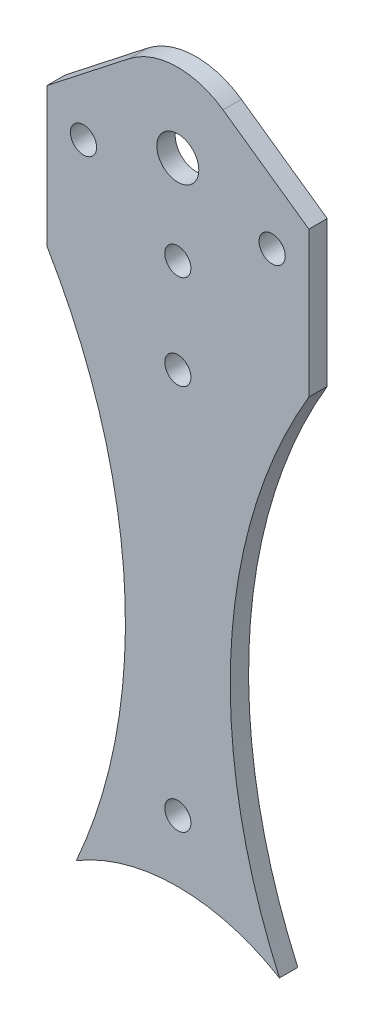
SolidWorks part; units mm, degrees
material "Cedar"
ref_plane "Front Plane" through (0, 0, 0) normal (0, 0, 1) x (1, 0, 0)
ref_plane "Top Plane" through (0, 0, 0) normal (0, 1, 0) x (1, 0, 0)
ref_plane "Right Plane" through (0, 0, 0) normal (1, 0, 0) x (0, 0, -1)
sketch "Sketch2" plane through (0, 0, 0) normal (0, 0, 1) x (1, 0, 0)
  line L0 (0, 112.1728) -> (0, -112.1727) construction
  line L1 (-31.75, 112.1728) -> (31.75, 112.1728)
  line L2 (-31.75, 112.1728) -> (-31.75, -112.1727)
  line L3 (-31.75, -112.1727) -> (31.75, -112.1727)
  line L4 (31.75, 112.1728) -> (31.75, -112.1727)
  line L5 (-31.75, 112.1728) -> (31.75, -112.1727) construction
  line L6 (-31.75, -112.1727) -> (31.75, 112.1728) construction
  line L7 (-31.75, 79.1528) -> (31.75, 79.1528) construction
  arc A0 (-31.75, -112.1727) -> (31.75, -112.1727) centre (0, -112.1727) ccw
  circle A1 centre (0, -112.1727) radius 6.35
  circle A2 centre (0, 86.7728) radius 5.08
  circle A3 centre (0, 65.1828) radius 3.175
  circle A4 centre (-22.86, 79.1528) radius 3.175
  circle A5 centre (22.86, 79.1528) radius 3.175
  arc A6 (-31.75, -86.7727) -> (-31.75, 52.4828) centre (-149.4697, -17.145) ccw
  arc A7 (31.75, -86.7727) -> (31.75, 52.4828) centre (149.4697, -17.145) cw
  point P0 (0, 0)
  point P25 (-12.7, -17.145)
  point P26 (12.7, -17.145)
  dimension "D1" = 12.7
  dimension "D3" = 10.16
  dimension "D4" = 6.35
  dimension "D8" = 6.35
  dimension "D9" = 6.35
  dimension "D13" = 25.4
  dimension "D15" = 25.4
  dimension "D2" = 63.5
  dimension "D5" = 21.59
  dimension "D6" = 13.97
  dimension "D7" = 22.86
  dimension "D10" = 22.86
  dimension "D11" = 198.9455
  dimension "D12" = 25.4
  dimension "D14" = 12.7
extrude "Boss-Extrude1" add sketch "Sketch2" along normal blind 4.445 contours L4 A7 L1 L2 A6 L3 A1 A2 A3 A4 A5 | A1 L3 A0
sketch "Sketch4" plane through (0, 0, 4.445) normal (0, 0, 1) x (1, 0, 0)
  line L0 (0, -143.9227) -> (0, 118.8593) construction
  arc A0 (-31.75, -112.1727) -> (31.75, -112.1727) centre (0, -112.1727) ccw construction
  circle A1 centre (0, 42.3228) radius 3.175
  circle A3 centre (0, -51.2127) radius 3.175
  circle A4 centre (0, -112.1727) radius 6.35 construction
  circle A5 centre (0, 86.7728) radius 5.08 construction
  dimension "D1" = 6.35
  dimension "D2" = 6.35
  dimension "D3" = 44.45
  dimension "D4" = 60.96
extrude "Cut-Extrude2" cut sketch "Sketch4" against normal through all
sketch "Sketch5" plane through (0, 0, 4.445) normal (0, 0, 1) x (1, 0, 0)
  line L0 (0, -112.1727) -> (0, -105.8227)
  circle A0 centre (0, -112.1727) radius 6.35 construction
  point P5 (0, 86.7728)
sketch "Sketch6" plane through (0, 0, 4.445) normal (0, 0, 1) x (1, 0, 0)
  circle A0 centre (0, -113.7602) radius 47.625
extrude "Cut-Extrude3" cut sketch "Sketch6" against normal through all
sketch "Sketch10" plane through (0, 0, 4.445) normal (0, 0, 1) x (1, 0, 0)
  line L0 (-31.75, 86.0944) -> (-11.7503, 101.7671)
  line L1 (-31.75, 112.1728) -> (-31.75, 52.4828) construction
  line L2 (31.75, 87.7279) -> (10.9613, 102.3533)
  line L3 (31.75, 112.1728) -> (31.75, 52.4827) construction
  line L4 (10.9613, 102.3533) -> (81.5289, 52.707) construction
  line L5 (-11.7503, 101.7671) -> (-79.6633, 48.5472) construction
  line L6 (-31.75, 86.0944) -> (-31.75, 125.449)
  line L7 (-31.75, 125.449) -> (31.75, 125.449)
  line L8 (31.75, 125.449) -> (31.75, 87.7279)
  circle A0 centre (0, 86.7728) radius 19.05
  line M3 (31.75, 52.4827) -> (31.75, 112.1728)
  line M4 (31.75, 112.1728) -> (-31.75, 112.1728)
  line M5 (-31.75, 112.1728) -> (-31.75, 52.4828)
  dimension "D1" = 38.1
extrude "Cut-Extrude4" cut sketch "Sketch10" against normal through all contours A0 L2 L0 M3 M4 M5
